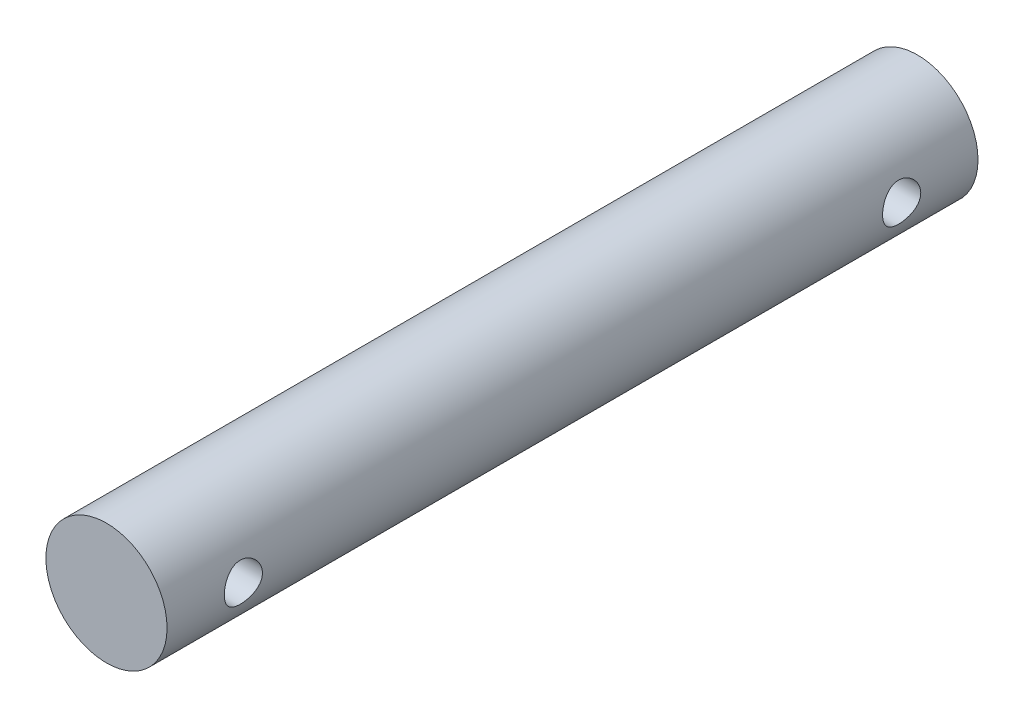
SolidWorks part; units mm, degrees
ref_plane "Alzado" through (0, 0, 0) normal (0, 0, 1) x (1, 0, 0)
ref_plane "Planta" through (0, 0, 0) normal (0, 1, 0) x (1, 0, 0)
ref_plane "Vista lateral" through (0, 0, 0) normal (1, 0, 0) x (0, 0, -1)
sketch "Croquis1" plane through (0, 0, 0) normal (0, 0, 1) x (1, 0, 0)
  circle A0 centre (0, 0) radius 6.35
  dimension "D1" = 12.7
extrude "Saliente-Extruir1" add sketch "Croquis1" along normal blind 85
sketch "Croquis2" plane through (0, 0, 0) normal (1, 0, 0) x (0, 0, -1)
  line L0 (-42.5, 6.35) -> (-42.5, -6.35) construction
  line L1 (0, 6.35) -> (-85, 6.35) construction
  line L2 (-85, -6.35) -> (0, -6.35) construction
  line L3 (0, 0) -> (-85, 0) construction
  line L4 (-85, 6.35) -> (-85, -6.35) construction
  circle A0 centre (-8, 0) radius 2
  circle A1 centre (-77, 0) radius 2
  dimension "D1" = 4
  dimension "D2" = 4
  dimension "D3" = 8
  dimension "D4" = 8
extrude "Cortar-Extruir1" cut sketch "Croquis2" against normal through all both and the other way through all
